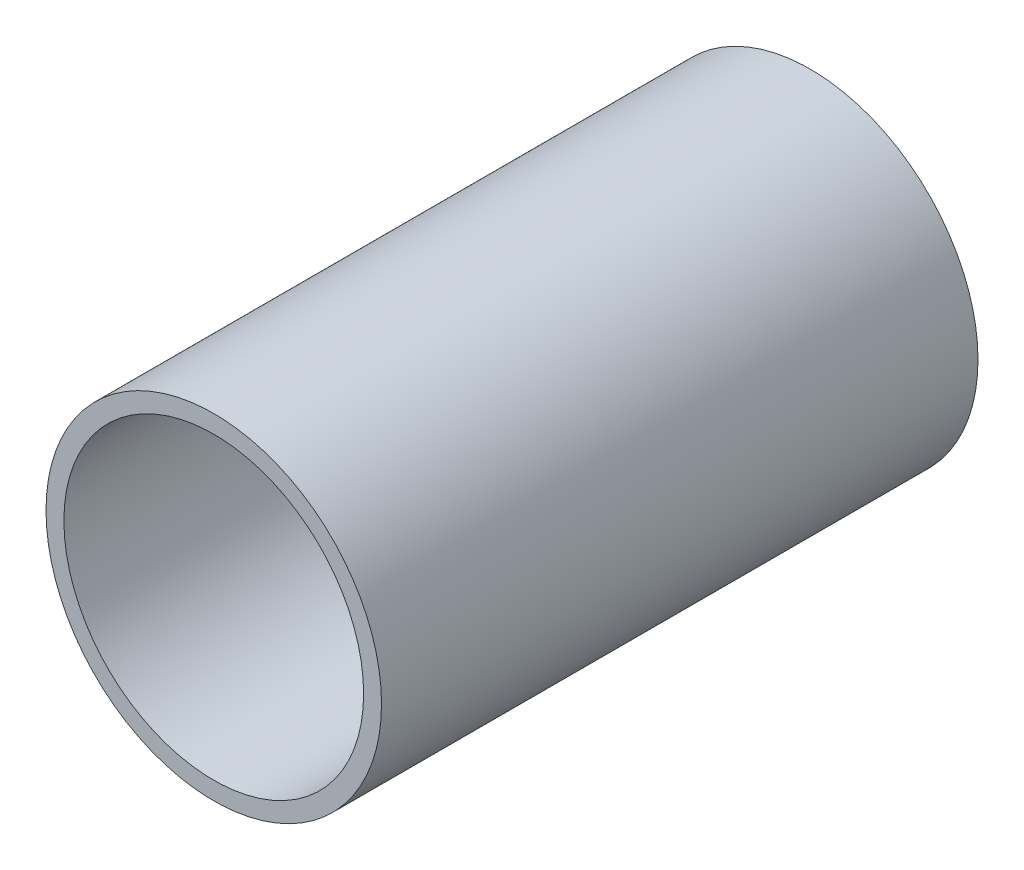
SolidWorks part; units mm, degrees
ref_plane "Front Plane" through (0, 0, 0) normal (0, 0, 1) x (1, 0, 0)
ref_plane "Top Plane" through (0, 0, 0) normal (0, 1, 0) x (1, 0, 0)
ref_plane "Right Plane" through (0, 0, 0) normal (1, 0, 0) x (0, 0, -1)
sketch "Sketch1" plane through (0, 0, 0) normal (0, 0, 1) x (1, 0, 0)
  circle A0 centre (0, 0) radius 28.575 construction
  circle A1 centre (0, 0) radius 25.527 construction
  point P3 (-28.575, 0)
  point P4 (28.575, 0)
  point P6 (-25.527, 0)
  point P7 (25.527, 0)
  dimension "OD" = 57.15
  dimension "Wall" = 3.048
  dimension "ID" = 51.054
sketch "Sketch2" plane through (0, 0, 0) normal (1, 0, 0) x (0, 0, -1)
  line L0 (50.8, 0) -> (-50.8, 0) construction
  line L2 (0, 28.575) -> (0, -28.575) construction
  line L3 (0, 28.575) -> (0, -28.575) construction
  line L4 (50.8, 28.575) -> (-50.8, 28.575) construction
  line L5 (50.8, -28.575) -> (-50.8, -28.575) construction
  line L6 (-50.8, -28.575) -> (-50.8, 28.575) construction
  line L7 (50.8, -28.575) -> (50.8, 28.575) construction
  line L8 (6.35, -28.575) -> (6.35, 28.575) construction
  line L9 (-6.35, -28.575) -> (-6.35, 28.575) construction
  point P3 (0, 0)
  point P9 (0, 28.575)
  point P11 (0, -28.575)
  point P13 (-50.8, 0)
  point P14 (50.8, 28.575)
  point P15 (-50.8, -28.575)
  point P16 (-50.8, 28.575)
  point P17 (-50.8, 0)
  point P18 (50.8, -28.575)
  point P19 (50.8, 0)
  point P22 (6.35, 0)
  point P25 (-6.35, 0)
  point P26 (6.35, -28.575)
  point P27 (6.35, 28.575)
  point P28 (-6.35, 28.575)
  point P29 (-6.35, -28.575)
  dimension "Length" = 101.6
  dimension "D1" = 57.15
sketch "Sketch3" plane through (0, 0, 0) normal (0, 0, 1) x (1, 0, 0)
  circle A0 centre (0, 0) radius 28.575 construction
  circle A1 centre (0, 0) radius 25.527 construction
  circle A2 centre (0, 0) radius 28.575
  circle A3 centre (0, 0) radius 25.527
extrude "Boss-Extrude1" add sketch "Sketch3" along normal mid plane 101.6
equation "\"D1@Sketch2\"=\"OD@Sketch1\""
equation "\"D1@Boss-Extrude1\"=\"Length@Sketch2\""
